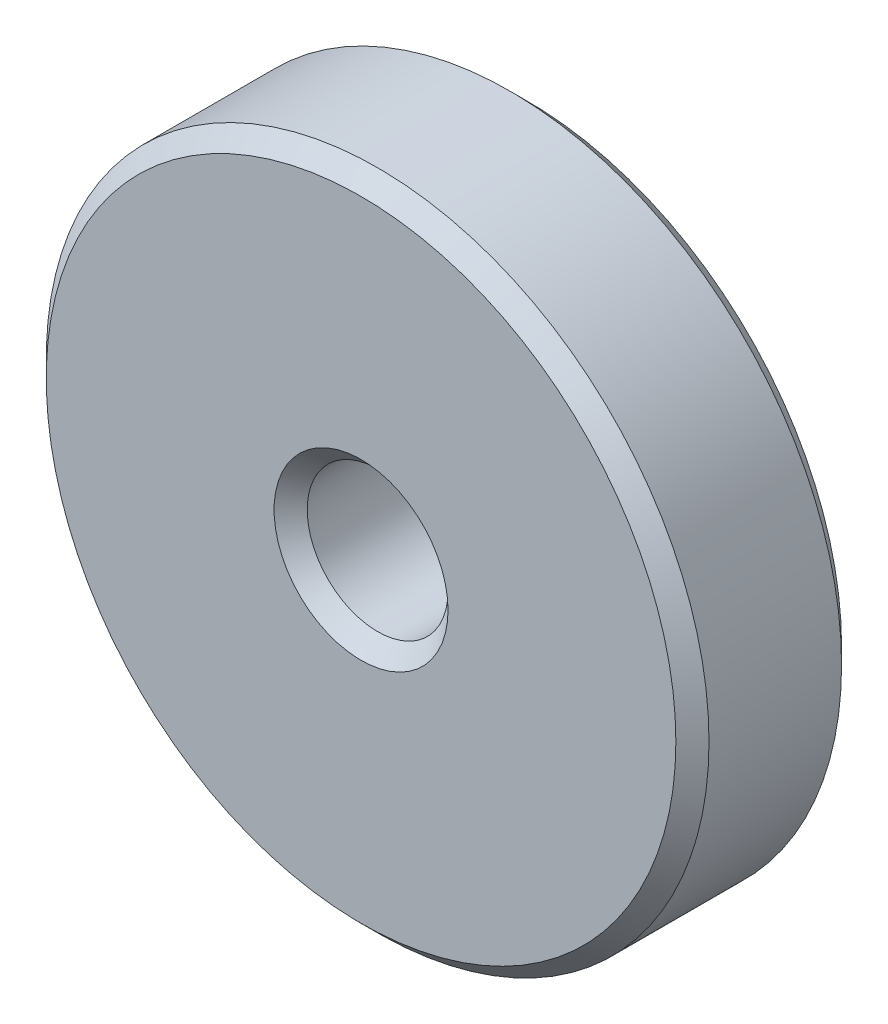
SolidWorks part; units mm, degrees
ref_plane "Płaszczyzna przednia" through (0, 0, 0) normal (0, 0, 1) x (1, 0, 0)
ref_plane "Płaszczyzna górna" through (0, 0, 0) normal (0, 1, 0) x (1, 0, 0)
ref_plane "Płaszczyzna prawa" through (0, 0, 0) normal (1, 0, 0) x (0, 0, -1)
sketch "Szkic1" plane through (0, 0, 0) normal (0, 0, 1) x (1, 0, 0)
  circle A0 centre (0, 0) radius 4.25
  circle A1 centre (0, 0) radius 20
  dimension "D1" = 8.5
  dimension "D2" = 40
extrude "Dodanie-wyciągnięcie1" add sketch "Szkic1" along normal blind 10
chamfer "Sfazowanie1" distance 1 angle 45 4 edges at (4.25, 0, 0) (20, 0, 0) (4.25, 0, 10) (20, 0, 10)
